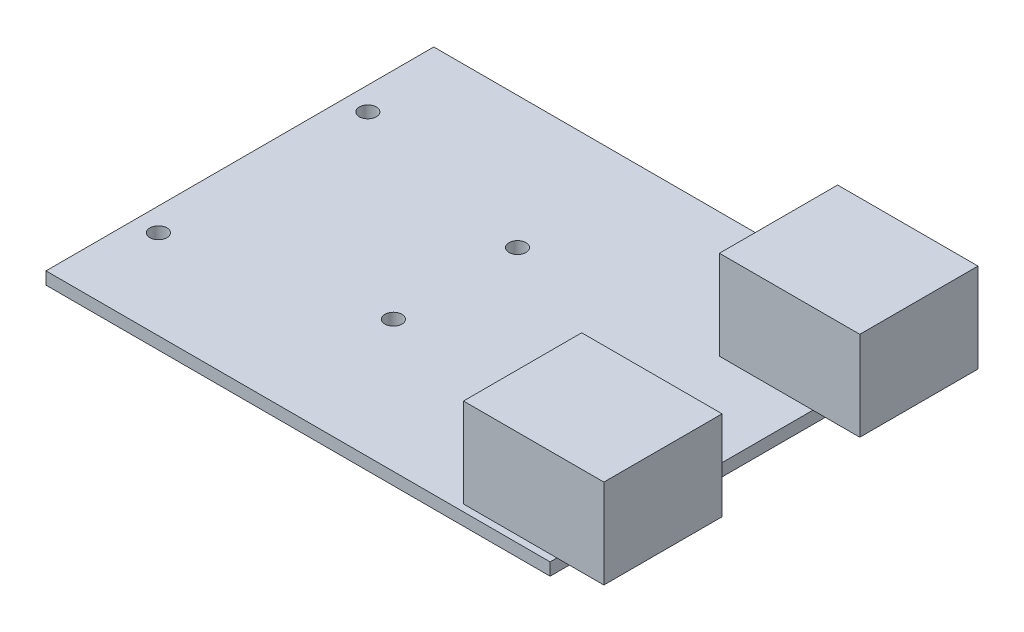
SolidWorks part; units mm, degrees
ref_plane "Front Plane" through (0, 0, 0) normal (0, 0, 1) x (1, 0, 0)
ref_plane "Top Plane" through (0, 0, 0) normal (0, 1, 0) x (1, 0, 0)
ref_plane "Right Plane" through (0, 0, 0) normal (1, 0, 0) x (0, 0, -1)
sketch "Sketch1" plane through (0, 0, 0) normal (0, 1, 0) x (1, 0, 0)
  line L1 (0, 0) -> (65, 0)
  line L2 (0, 0) -> (0, 50)
  line L3 (0, 50) -> (65, 50)
  line L4 (65, 0) -> (65, 50)
  dimension "D1" = 50
  dimension "D2" = 65
extrude "Boss-Extrude1" add sketch "Sketch1" along normal blind 1.6002
hole_wizard "Ø2.5mm Dowel Hole1" positions "Sketch3" profile "Sketch2" hole size "Ø2.5" standard "ANSI Metric" end condition through all
sketch "Sketch3" plane through (0, 1.6002, 0) normal (0, 1, 0) x (1, 0, 0)
  line L0 (0, 50) -> (0, 0) construction
  line L1 (0, 0) -> (65, 0) construction
  point P0 (3, 11.5)
  point P2 (3, 38.5)
  point P4 (27.8, 17)
  point P6 (27.8, 33)
  dimension "D1" = 3
  dimension "D2" = 11.5
  dimension "D3" = 38.5
  dimension "D4" = 17
  dimension "D5" = 27.8
  dimension "D6" = 33
sketch "Sketch2" plane through (3, 1.6002, -11.5) normal (1, 0, 0) x (0, 0, 1)
  line L0 (0, 0) -> (0, 1.6002)
  line L1 (0, 1.6002) -> (1.1, 1.6002)
  line L2 (1.1, 1.6002) -> (1.1, 0)
  line L5 (1.1, 0) -> (0, 0)
  line L11 (0, -6.35) -> (0, 107.95) construction
  dimension "Thru Hole Dia." = 2.2
  dimension "Thru Hole Depth" = 1.6002
sketch "Sketch4" plane through (0, 1.6002, 0) normal (0, 1, 0) x (1, 0, 0)
  line L0 (0, 50) -> (0, 0) construction
  line L1 (52.95, 33.88) -> (71.05, 33.88)
  line L2 (52.95, 33.88) -> (52.95, 49.12)
  line L3 (52.95, 49.12) -> (71.05, 49.12)
  line L4 (71.05, 33.88) -> (71.05, 49.12)
  line L5 (52.95, 33.88) -> (71.05, 49.12) construction
  line L6 (52.95, 49.12) -> (71.05, 33.88) construction
  line L7 (0, 0) -> (65, 0) construction
  line L9 (52.95, 0.88) -> (71.05, 0.88)
  line L10 (52.95, 0.88) -> (52.95, 16.12)
  line L11 (52.95, 16.12) -> (71.05, 16.12)
  line L12 (71.05, 0.88) -> (71.05, 16.12)
  line L13 (52.95, 0.88) -> (71.05, 16.12) construction
  line L14 (52.95, 16.12) -> (71.05, 0.88) construction
  point P0 (62, 41.5)
  point P9 (62, 8.5)
  dimension "D1" = 15.24
  dimension "D2" = 18.1
  dimension "D3" = 62
  dimension "D4" = 41.5
  dimension "D5" = 8.5
extrude "Boss-Extrude2" add sketch "Sketch4" along normal blind 11.5
